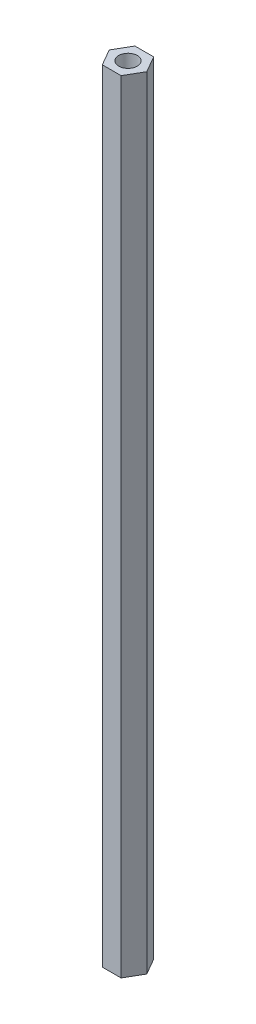
SolidWorks part; units mm, degrees
ref_plane "Front Plane" through (0, 0, 0) normal (0, 0, 1) x (1, 0, 0)
ref_plane "Top Plane" through (0, 0, 0) normal (0, 1, 0) x (1, 0, 0)
ref_plane "Right Plane" through (0, 0, 0) normal (1, 0, 0) x (0, 0, -1)
sketch "Sketch1" plane through (0, 0, 0) normal (0, 1, 0) x (1, 0, 0)
  line L1 (-2.0207, 3.5) -> (-4.0415, 0)
  line L2 (-4.0415, 0) -> (-2.0207, -3.5)
  line L3 (-2.0207, -3.5) -> (2.0207, -3.5)
  line L4 (2.0207, -3.5) -> (4.0415, 0)
  line L5 (4.0415, 0) -> (2.0207, 3.5)
  line L6 (2.0207, 3.5) -> (-2.0207, 3.5)
  circle A0 centre (0, 0) radius 3.5 construction
  circle A1 centre (0, 0) radius 2
  dimension "D1" = 7
  dimension "D2" = 4
extrude "Boss-Extrude1" add sketch "Sketch1" along normal blind 168
